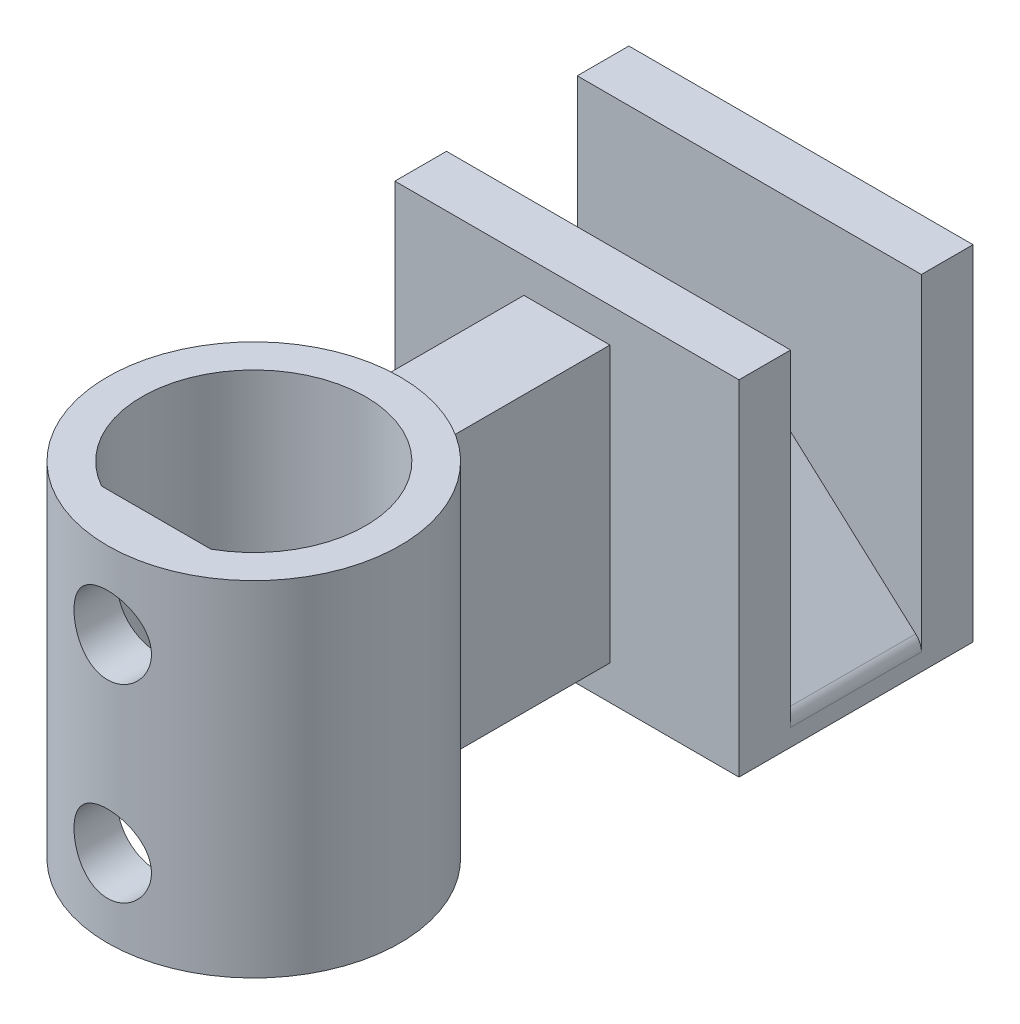
SolidWorks part; units mm, degrees
material "ABS"
ref_plane "Front Plane" through (0, 0, 0) normal (0, 0, 1) x (1, 0, 0)
ref_plane "Top Plane" through (0, 0, 0) normal (0, 1, 0) x (1, 0, 0)
ref_plane "Right Plane" through (0, 0, 0) normal (1, 0, 0) x (0, 0, -1)
sketch "Sketch2" plane through (0, 0, 0) normal (0, 0, 1) x (1, 0, 0)
  line L1 (-10, -5) -> (10, -5)
  line L2 (-10, -5) -> (-10, 5)
  line L3 (-10, 5) -> (10, 5)
  line L4 (10, -5) -> (10, 5)
  line L5 (-10, -5) -> (10, 5) construction
  line L6 (-10, 5) -> (10, -5) construction
  point P0 (0, 0)
  dimension "D1" = 10
  dimension "D2" = 20
extrude "Boss-Extrude1" add sketch "Sketch2" along normal mid plane 7.6
chamfer "Chamfer1" distance 9.5 angle 42 2 edges at (10, 5, 0) (-10, 5, 0)
fillet "Fillet3" radius 1 4 edges at (-10, -3.5538, 0) (10, -3.5538, 0) (0.5, 5, 0) (-0.5, 5, 0)
sketch "Sketch3" plane through (0, 0, 3.8) normal (0, 0, 1) x (1, 0, 0)
  line L0 (-10, -5) -> (10, -5) construction
  line L1 (-10, 15) -> (10, 15)
  line L2 (-10, 15) -> (-10, -5)
  line L3 (-10, -5) -> (10, -5)
  line L4 (10, 15) -> (10, -5)
  line L5 (-10, 15) -> (10, -5) construction
  line L6 (-10, -5) -> (10, 15) construction
  point P0 (0, 5)
  dimension "D1" = 20
  dimension "D2" = 20
extrude "Boss-Extrude2" add sketch "Sketch3" along normal blind 3
mirror "Mirror1" about plane through (0, 0, 0) normal (0, 0, 1) of "Boss-Extrude2"
sketch "Sketch6" plane through (0, 0, 0) normal (0, 1, 0) x (1, 0, 0)
  line L0 (3.175, -30.6718) -> (-3.175, -30.6718)
  arc A0 (3.175, -30.6718) -> (-3.175, -30.6718) centre (0, -25) ccw
  circle A1 centre (0, -25) radius 8.5
  dimension "D1" = 13
  dimension "D2" = 2
  dimension "D3" = 25
  dimension "D4" = 6.35
extrude "Boss-Extrude3" add sketch "Sketch6" along normal up to surface and the other way up to surface separate body up to face at (0, 15, 5.3) other way up to face at (0, -5, 0)
sketch "Sketch5" plane through (0, 0, 6.8) normal (0, 0, 1) x (1, 0, 0)
  line L0 (-10, -5) -> (10, -5) construction
  line L1 (-2.5, 13) -> (2.5, 13)
  line L2 (-2.5, 13) -> (-2.5, -3)
  line L3 (-2.5, -3) -> (2.5, -3)
  line L4 (2.5, 13) -> (2.5, -3)
  line L5 (-2.5, 13) -> (2.5, -3) construction
  line L6 (-2.5, -3) -> (2.5, 13) construction
  line L7 (10, 15) -> (-10, 15) construction
  point P0 (0, 5)
  dimension "D1" = 2
  dimension "D2" = 2
  dimension "D3" = 5
extrude "Boss-Extrude4" add sketch "Sketch5" along normal up to surface (10.076 mm away)
ref_plane "Plane1" through (0, 0, 20) normal (0, 0, 1) x (1, 0, 0)
sketch "Sketch7" plane through (0, 0, 20) normal (0, 0, 1) x (1, 0, 0)
  line L0 (-8.5, -5) -> (8.5, -5) construction
  line L1 (6.5, 15) -> (-6.5, 15) construction
  circle A0 centre (0, 10.5) radius 2.25
  circle A1 centre (0, -0.5) radius 2.25
  dimension "D1" = 4.5
  dimension "D2" = 4.5
  dimension "D3" = 4.5
  dimension "D4" = 4.5
extrude "Cut-Extrude1" cut sketch "Sketch7" along normal up to surface (13.1968 mm away)
